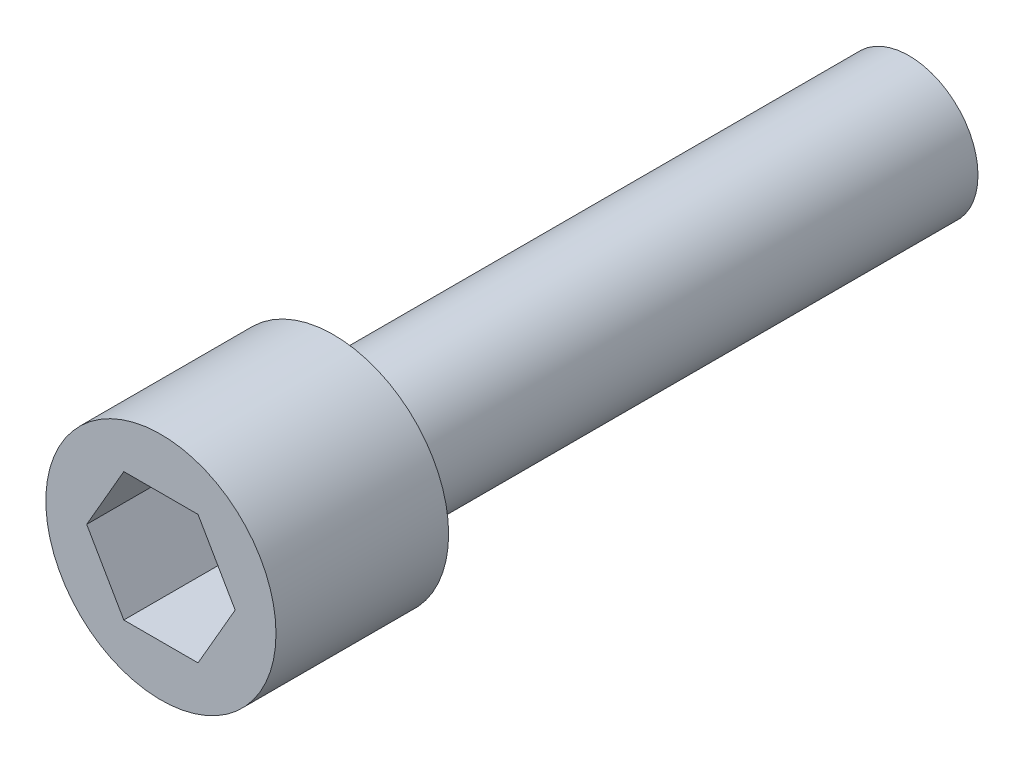
SolidWorks part; units mm, degrees
ref_plane "Front Plane" through (0, 0, 0) normal (0, 0, 1) x (1, 0, 0)
ref_plane "Top Plane" through (0, 0, 0) normal (0, 1, 0) x (1, 0, 0)
ref_plane "Right Plane" through (0, 0, 0) normal (1, 0, 0) x (0, 0, -1)
sketch "Sketch1" plane through (0, 0, 0) normal (0, 0, 1) x (1, 0, 0)
  circle A0 centre (-15, 15) radius 1.2
extrude "Boss-Extrude1" add sketch "Sketch1" against normal blind 10
sketch "Sketch2" plane through (0, 0, 0) normal (0, 0, 1) x (1, 0, 0)
  circle A0 centre (-15, 15) radius 2
extrude "Boss-Extrude2" add sketch "Sketch2" along normal blind 3
sketch "Sketch3" plane through (0, 0, 3) normal (0, 0, 1) x (1, 0, 0)
  line L1 (-13.7099, 15) -> (-14.355, 16.1172)
  line L2 (-14.355, 16.1172) -> (-15.645, 16.1172)
  line L3 (-15.645, 16.1172) -> (-16.2901, 15)
  line L4 (-16.2901, 15) -> (-15.645, 13.8828)
  line L5 (-15.645, 13.8828) -> (-14.355, 13.8828)
  line L6 (-14.355, 13.8828) -> (-13.7099, 15)
  circle A0 centre (-15, 15) radius 1.1172 construction
extrude "Cut-Extrude1" cut sketch "Sketch3" against normal blind 2
